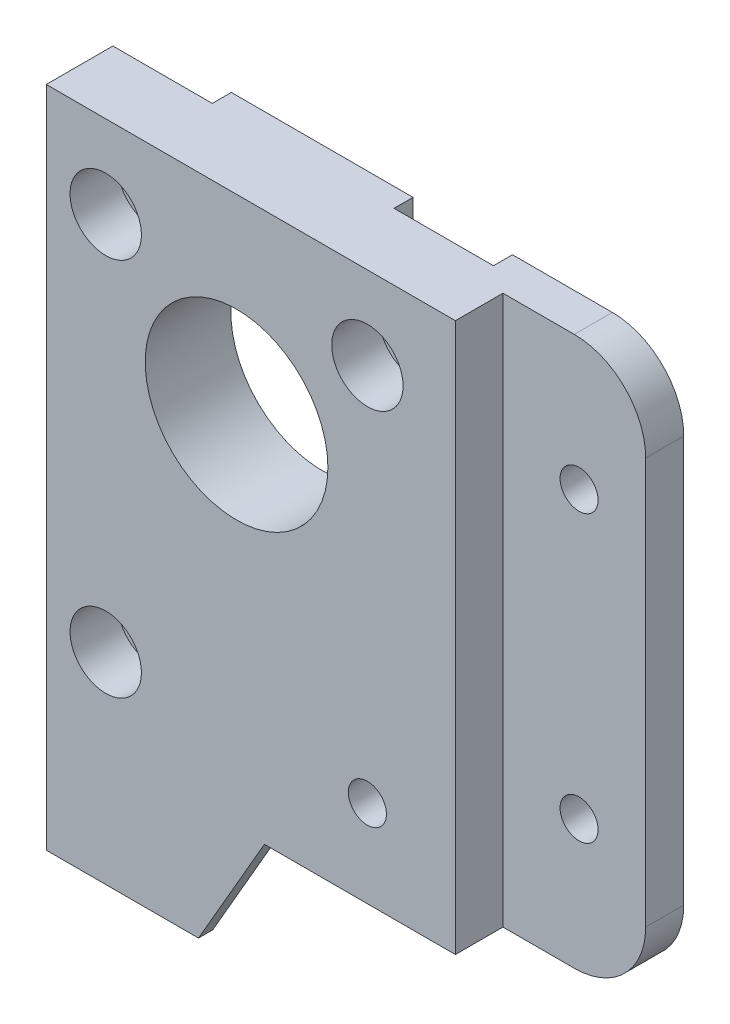
SolidWorks part; units mm, degrees
material "Custom Plastic"
ref_plane "Front Plane" through (0, 0, 0) normal (0, 0, 1) x (1, 0, 0)
ref_plane "Top Plane" through (0, 0, 0) normal (0, 1, 0) x (1, 0, 0)
ref_plane "Right Plane" through (0, 0, 0) normal (1, 0, 0) x (0, 0, -1)
sketch "Sketch1" plane through (0, 0, 0) normal (0, 0, 1) x (1, 0, 0)
  line L0 (-13.75, -19.7) -> (-9.788, -16.65) construction
  line L3 (20, 28.85) -> (38, 28.85)
  line L8 (20, -28.85) -> (-20, -28.85)
  line L9 (20, -28.85) -> (20, 28.85) construction
  line L10 (38, 28.85) -> (38, -28.85)
  line L11 (20, 28.85) -> (-20, 28.85)
  line L14 (-20, -28.85) -> (-20, 28.85)
  line L15 (20, -28.85) -> (-20, 28.85) construction
  line L16 (20, 28.85) -> (-20, -28.85) construction
  line L17 (-16.312, -16.3719) -> (-12.35, -13.3219)
  line L18 (-11.188, -23.0281) -> (-7.226, -19.9781)
  line L19 (0, -28.85) -> (0, 28.85) construction
  line L22 (38, -28.85) -> (20, -28.85)
  line L23 (17.2017, -17.3071) -> (20, -21.3437)
  line L24 (9.55, -19.7) -> (9.55, -28.85)
  line L25 (-9.55, 20.15) -> (-9.55, 28.85)
  line L26 (-17.2017, 17.7571) -> (-20, 21.7937)
  line L27 (9.55, 20.15) -> (9.55, 28.85)
  line L28 (17.2017, 17.7571) -> (20, 21.7937)
  line L29 (20, 21.7937) -> (20, 28.85)
  line L30 (-16.312, -16.3719) -> (-20, -16.3719)
  line L31 (20, -28.85) -> (20, -21.3437)
  line L33 (-13.75, -23.9) -> (-13.75, -28.85)
  circle A18 centre (-13.75, 20.15) radius 4.2
  circle A19 centre (13.75, 20.15) radius 4.2
  circle A20 centre (13.75, -19.7) radius 4.2
  arc A21 (-16.312, -16.3719) -> (-11.188, -23.0281) centre (-13.75, -19.7) ccw
  arc A22 (-7.226, -19.9781) -> (-12.35, -13.3219) centre (-9.788, -16.65) ccw
  circle A23 centre (0, 8.8) radius 9.6
  circle A24 centre (-5.725, -6.1) radius 4.2
  circle A25 centre (5.725, -6.1) radius 4.2
  point P0 (0, 0)
  point P14 (-6.4599, -14.088)
  point P31 (-11.769, -18.175)
  point P37 (5.725, -10.3)
  point P43 (20, 28.85)
  point P46 (-20, 28.85)
  dimension "D1" = 57.7
  dimension "D2" = 40
  dimension "D3" = 12.2
  dimension "D4" = 8.4
  dimension "D5" = 8.4
  dimension "D6" = 19.2
  dimension "D7" = 9.15
  dimension "D8" = 27.5
  dimension "D9" = 39.85
  dimension "D10" = 5
  dimension "D12" = 20.05
  dimension "D13" = 11.45
  dimension "D14" = 22.75
  dimension "D15" = 18
extrude "Boss-Extrude1" add sketch "Sketch1" along normal blind 2
sketch "Sketch4" plane through (0, 0, 2) normal (0, 0, 1) x (1, 0, 0)
  line L0 (0, -28.85) -> (0, 29) construction
  line L6 (38, -28.85) -> (20, -28.85) construction
  line L8 (-20, -28.85) -> (38, -28.85)
  line L11 (38, -28.85) -> (38, 28.85)
  line L12 (-20, 28.85) -> (-20, -28.85)
  line L13 (-20, -16.3719) -> (-20, 21.7937) construction
  line L14 (-20, 28.85) -> (38, 28.85)
  line L15 (20, 28.85) -> (38, 28.85) construction
  line L16 (38, 28.85) -> (38, -28.85) construction
  circle A2 centre (13.75, -19.7) radius 2
  circle A3 centre (-13.75, 20.15) radius 2
  circle A4 centre (13.75, 20.15) radius 2
  circle A10 centre (-13.75, -19.7) radius 2
  circle A11 centre (0, 8.8) radius 9.6
  circle A12 centre (0, 8.8) radius 9.6 construction
  dimension "D1" = 4
extrude "Boss-Extrude3" add sketch "Sketch4" along normal blind 2
sketch "Sketch5" plane through (0, 0, 4) normal (0, 0, 1) x (1, 0, 0)
  line L0 (-20, 0) -> (38, 0) construction
  line L3 (-20, 28.85) -> (-20, -28.85) construction
  line L4 (38, -28.85) -> (38, 28.85) construction
  circle A0 centre (31, 15) radius 2
  circle A1 centre (31, -15) radius 2
  dimension "D1" = 4
  dimension "D2" = 15
  dimension "D3" = 51
extrude "Cut-Extrude1" cut sketch "Sketch5" against normal blind 4
ref_plane "Plane1" through (0, 0, 0) normal (0, 0, -1) x (-1, 0, 0)
sketch "Sketch6" plane through (0, 0, 4) normal (0, 0, 1) x (1, 0, 0)
  line L0 (23, 28.85) -> (23, -28.85)
  line L1 (38, 28.85) -> (-20, 28.85) construction
  line L2 (-20, -28.85) -> (38, -28.85) construction
  line L3 (38, -28.85) -> (38, 28.85) construction
  circle A52 centre (-13.75, 20.15) radius 3.75
  circle A53 centre (13.75, 20.15) radius 3.75
  circle A54 centre (31, 15) radius 2
  circle A55 centre (13.75, -19.7) radius 3.75
  circle A56 centre (-13.75, -19.7) radius 3.75
  circle A57 centre (31, -15) radius 2
  circle A59 centre (31, 15) radius 2 construction
  circle A60 centre (31, -15) radius 2 construction
  line M5 (-20, 28.85) -> (-20, -28.85)
  line M6 (-20, -28.85) -> (38, -28.85)
  line M7 (38, -28.85) -> (38, 28.85)
  line M8 (38, 28.85) -> (-20, 28.85)
  circle M9 centre (13.75, -19.7) radius 2
  circle M11 centre (0, 8.8) radius 9.6
  dimension "D1" = 7.5
  dimension "D2" = 15
extrude "Boss-Extrude4" add sketch "Sketch6" along normal blind 5 contours A57 A56 A55 A54 A53 A52 M8 M5 M6 M7 M11 | A55 M9
sketch "Sketch7" plane through (0, 0, 4) normal (0, 0, 1) x (1, 0, 0)
  line L0 (38, -28.85) -> (38, 28.85) construction
  line L1 (30.5, 28.85) -> (38, 28.85)
  line L2 (38, 28.85) -> (38, 21.35)
  line L3 (-20, 0) -> (38, 0) construction
  line L4 (-20, 28.85) -> (-20, -28.85) construction
  line L5 (38, -28.85) -> (38, -21.35)
  line L6 (30.5, -28.85) -> (38, -28.85)
  arc A0 (38, 21.35) -> (30.5, 28.85) centre (30.5, 21.35) ccw
  arc A1 (38, -21.35) -> (30.5, -28.85) centre (30.5, -21.35) cw
  dimension "D1" = 15
extrude "Cut-Extrude2" cut sketch "Sketch7" against normal through all
sketch "Sketch9" plane through (-20, 0, 0) normal (-1, 0, 0) x (0, 0, 1)
  line L0 (9, -28.85) -> (9, -40.85)
  line L2 (9, -40.85) -> (0, -40.85)
  line L3 (0, -40.85) -> (0, -35.15)
  line L4 (0, -35.15) -> (3, -35.15)
  line L5 (3, -35.15) -> (3, -28.85)
  line L6 (9, -28.85) -> (2, -28.85) construction
  line L7 (0, -16.3719) -> (0, 21.7937) construction
  line L9 (3, -28.85) -> (9, -28.85)
  dimension "D1" = 6
  dimension "D2" = 12
  dimension "D3" = 6.3
extrude "Boss-Extrude5" add sketch "Sketch9" against normal blind 6
sketch "Sketch10" plane through (0, 0, 9) normal (0, 0, 1) x (1, 0, 0)
  line L0 (-14, -40.85) -> (-4, -40.85)
  line L1 (-4, -40.85) -> (2.9282, -28.85)
  line L3 (2.9282, -28.85) -> (-14, -28.85)
  line L4 (-14, -28.85) -> (-14, -40.85)
  dimension "D1" = 10
  dimension "D2" = 120
extrude "Boss-Extrude6" add sketch "Sketch10" against normal blind 1.5
